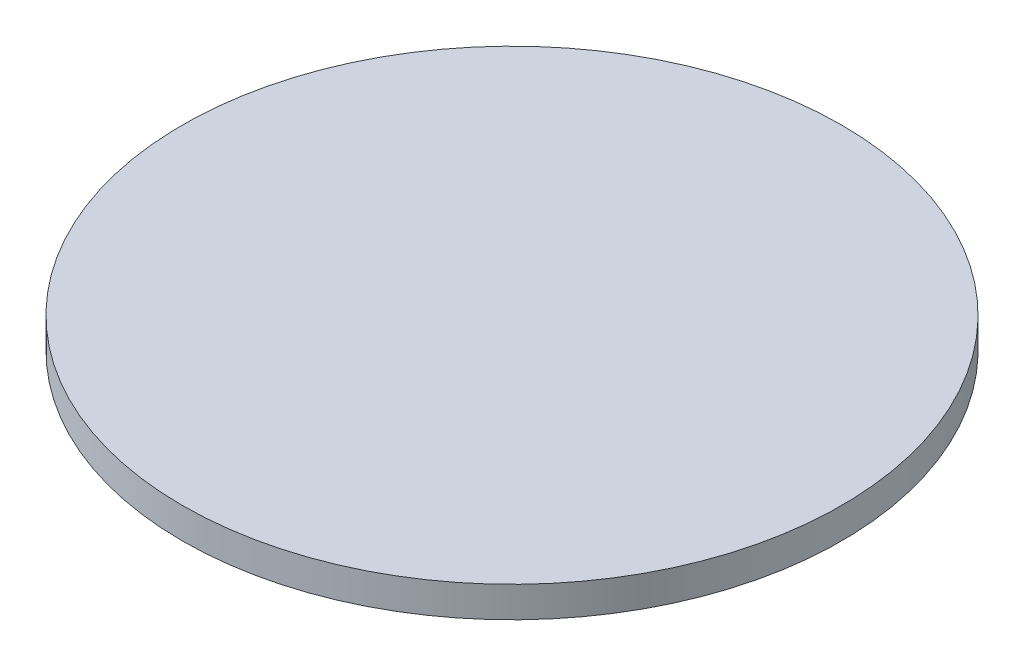
SolidWorks part; units mm, degrees
ref_plane "Front Plane" through (0, 0, 0) normal (0, 0, 1) x (1, 0, 0)
ref_plane "Top Plane" through (0, 0, 0) normal (0, 1, 0) x (1, 0, 0)
ref_plane "Right Plane" through (0, 0, 0) normal (1, 0, 0) x (0, 0, -1)
sketch "Gel Pad Sketch" plane through (0, 0, 97.3) normal (0, 1, 0) x (1, 0, 0)
  circle A0 centre (0, 97.3) radius 16.073
extrude "Gel Pad" add sketch "Gel Pad Sketch" along normal blind 1.5
